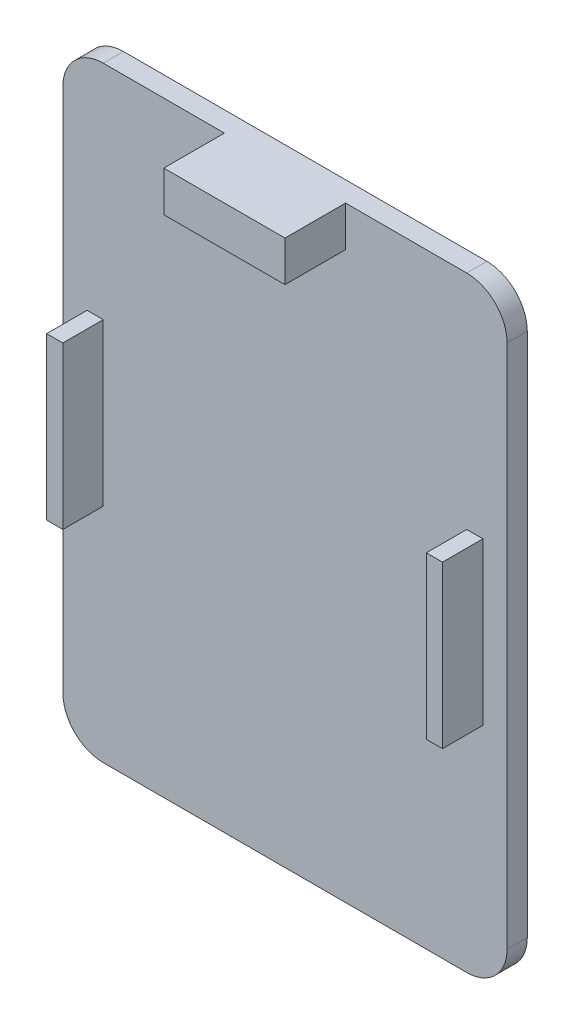
SolidWorks part; units mm, degrees
ref_plane "Front Plane" through (0, 0, 0) normal (0, 0, 1) x (1, 0, 0)
ref_plane "Top Plane" through (0, 0, 0) normal (0, 1, 0) x (1, 0, 0)
ref_plane "Right Plane" through (0, 0, 0) normal (1, 0, 0) x (0, 0, -1)
sketch "Sketch1" plane through (0, 0, 0) normal (0, 0, 1) x (1, 0, 0)
  line L1 (-4.5, -7.5) -> (4.5, -7.5)
  line L2 (-5.5, -6.5) -> (-5.5, 6.5)
  line L3 (-4.5, 7.5) -> (4.5, 7.5)
  line L4 (5.5, -6.5) -> (5.5, 6.5)
  line L5 (-5.5, -7.5) -> (5.5, 7.5) construction
  line L6 (-5.5, 7.5) -> (5.5, -7.5) construction
  arc A0 (4.5, 7.5) -> (5.5, 6.5) centre (4.5, 6.5) cw
  arc A1 (5.5, -6.5) -> (4.5, -7.5) centre (4.5, -6.5) cw
  arc A2 (-4.5, -7.5) -> (-5.5, -6.5) centre (-4.5, -6.5) cw
  arc A3 (-4.5, 7.5) -> (-5.5, 6.5) centre (-4.5, 6.5) ccw
  point P0 (0, 0)
  dimension "D3" = 1
  dimension "D1" = 11
  dimension "D2" = 15
extrude "Boss-Extrude1" add sketch "Sketch1" along normal blind 0.5
sketch "Sketch2" plane through (0, 0, 0.5) normal (0, 0, 1) x (1, 0, 0)
  line L0 (4.5, 7.5) -> (-4.5, 7.5) construction
  line L1 (-1.5, 7.5) -> (1.5, 7.5)
  line L2 (-1.5, 7.5) -> (-1.5, 6.5)
  line L3 (-1.5, 6.5) -> (1.5, 6.5)
  line L4 (1.5, 7.5) -> (1.5, 6.5)
  dimension "D1" = 3
  dimension "D2" = 1.5
  dimension "D3" = 1.5
  dimension "D4" = 1
extrude "Boss-Extrude2" add sketch "Sketch2" along normal blind 1.5
sketch "Sketch3" plane through (0, 0, 0.5) normal (0, 0, 1) x (1, 0, 0)
  line L0 (-5.5, 6.5) -> (-5.5, -6.5) construction
  line L1 (-4.9, 2) -> (-4.5, 2)
  line L2 (-4.9, 2) -> (-4.9, -2)
  line L3 (-4.9, -2) -> (-4.5, -2)
  line L4 (-4.5, 2) -> (-4.5, -2)
  dimension "D1" = 0.6
  dimension "D2" = 4
  dimension "D3" = 2
  dimension "D4" = 0.4
extrude "Boss-Extrude3" add sketch "Sketch3" along normal blind 1
mirror "Mirror2" about plane through (0, 0, 0) normal (1, 0, 0) of "Boss-Extrude3"
